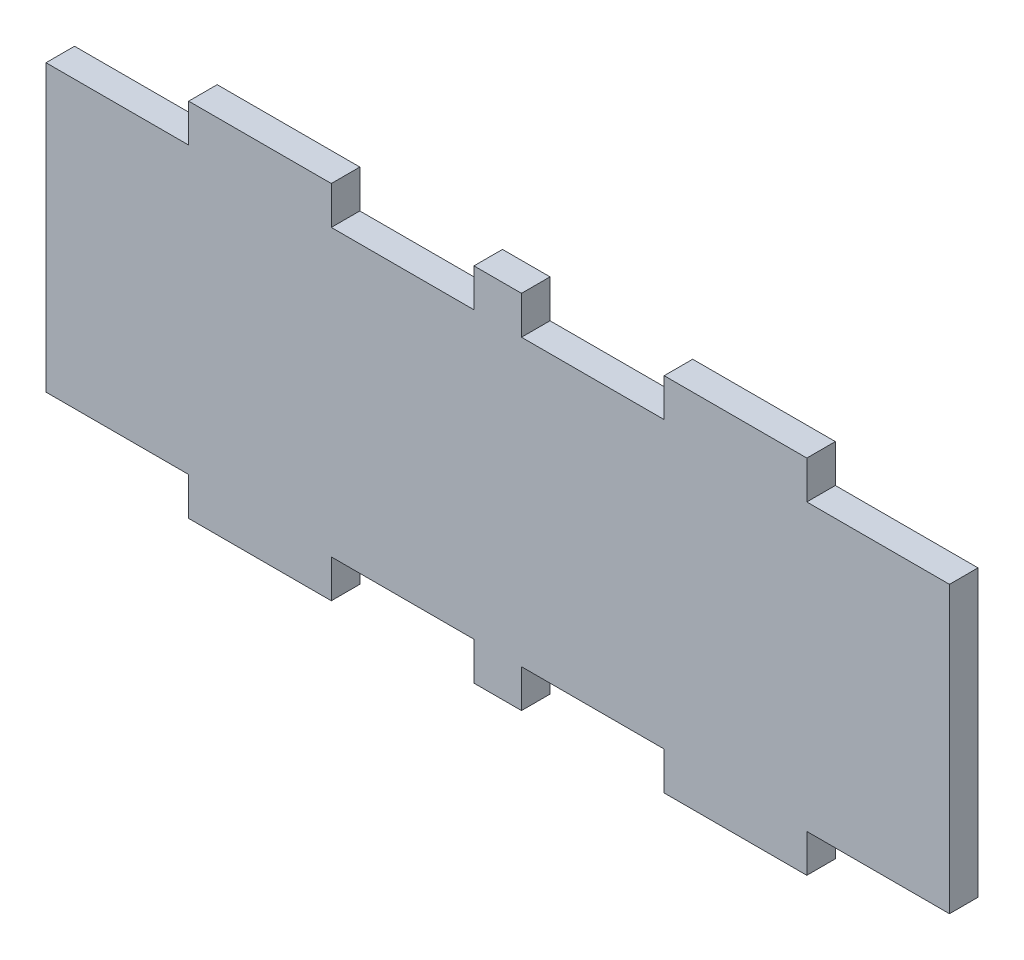
SolidWorks part; units mm, degrees
ref_plane "Front Plane" through (0, 0, 0) normal (0, 0, 1) x (1, 0, 0)
ref_plane "Top Plane" through (0, 0, 0) normal (0, 1, 0) x (1, 0, 0)
ref_plane "Right Plane" through (0, 0, 0) normal (1, 0, 0) x (0, 0, -1)
sketch "Sketch1" plane through (0, 0, 0) normal (0, 0, 1) x (1, 0, 0)
  line L1 (0, 0) -> (-95, 0)
  line L2 (0, 0) -> (0, 30)
  line L3 (0, 30) -> (-95, 30)
  line L4 (-95, 0) -> (-95, 30)
  dimension "D1" = 30
  dimension "D2" = 95
extrude "Boss-Extrude1" add sketch "Sketch1" along normal blind 3
sketch "Sketch3" plane through (0, 0, 3) normal (0, 0, 1) x (1, 0, 0)
  line L3 (0, 34) -> (-95, 34)
  line L4 (-15, 34) -> (-30, 34)
  line L5 (-80, 30) -> (-65, 30)
  line L7 (-80, 34) -> (-80, 30)
  line L8 (-15, 34) -> (-15, 30)
  line L9 (-30, 34) -> (-30, 30)
  line L10 (-65, 34) -> (-65, 30)
  line L11 (-50, 34) -> (-50, 30)
  line L12 (-45, 34) -> (-45, 30)
  line L13 (-65, 34) -> (-80, 34)
  line L14 (-50, 30) -> (-45, 30)
  line L15 (-45, 34) -> (-50, 34)
  line L16 (-30, 30) -> (-15, 30)
  line L17 (-95, 15) -> (0, 15) construction
  line L18 (-95, 30) -> (-95, 0) construction
  line L19 (0, 0) -> (0, 30) construction
  line L20 (-30, 0) -> (-15, 0)
  line L21 (-45, -4) -> (-50, -4)
  line L22 (-50, 0) -> (-45, 0)
  line L23 (-65, -4) -> (-80, -4)
  line L24 (-45, -4) -> (-45, 0)
  line L25 (-50, -4) -> (-50, 0)
  line L26 (-65, -4) -> (-65, 0)
  line L27 (-30, -4) -> (-30, 0)
  line L28 (-15, -4) -> (-15, 0)
  line L29 (-80, -4) -> (-80, 0)
  line L30 (-80, 0) -> (-65, 0)
  line L31 (-15, -4) -> (-30, -4)
  dimension "D3" = 15
  dimension "D5" = 15
  dimension "D6" = 15
  dimension "D7" = 15
  dimension "D1" = 4
extrude "Boss-Extrude2" add sketch "Sketch3" against normal blind 3
